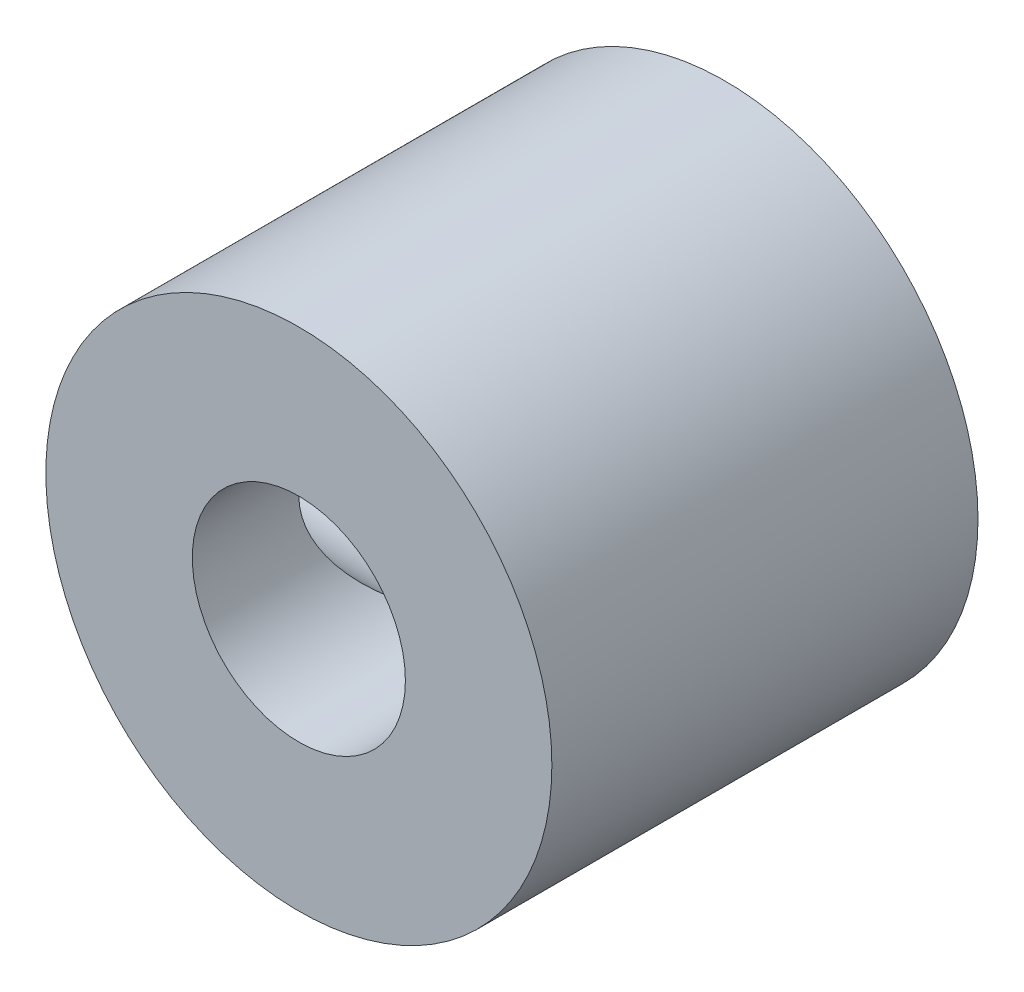
SolidWorks part; units mm, degrees
ref_plane "前视基准面" through (0, 0, 0) normal (0, 0, 1) x (1, 0, 0)
ref_plane "上视基准面" through (0, 0, 0) normal (0, 1, 0) x (1, 0, 0)
ref_plane "右视基准面" through (0, 0, 0) normal (1, 0, 0) x (0, 0, -1)
sketch "草图1" plane through (0, 0, 0) normal (0, 0, 1) x (1, 0, 0)
  circle A0 centre (0, 0) radius 4.75
  circle A1 centre (0, 0) radius 2
  dimension "D1" = 9.5
  dimension "D2" = 4
extrude "凸台-拉伸1" add sketch "草图1" along normal blind 8
sketch "草图2" plane through (0, 0, 0) normal (1, 0, 0) x (0, 0, -1)
  line L0 (-8, 0) -> (0, 0) construction
  line L1 (-8, 4.75) -> (-8, -4.75) construction
  line L2 (-4, 4.75) -> (-4, -4.75) construction
  line L3 (0, 4.75) -> (-8, 4.75) construction
  line L4 (-8, -4.75) -> (0, -4.75) construction
  circle A0 centre (-4, 0) radius 2
extrude "切除-拉伸1" cut sketch "草图2" against normal through all
